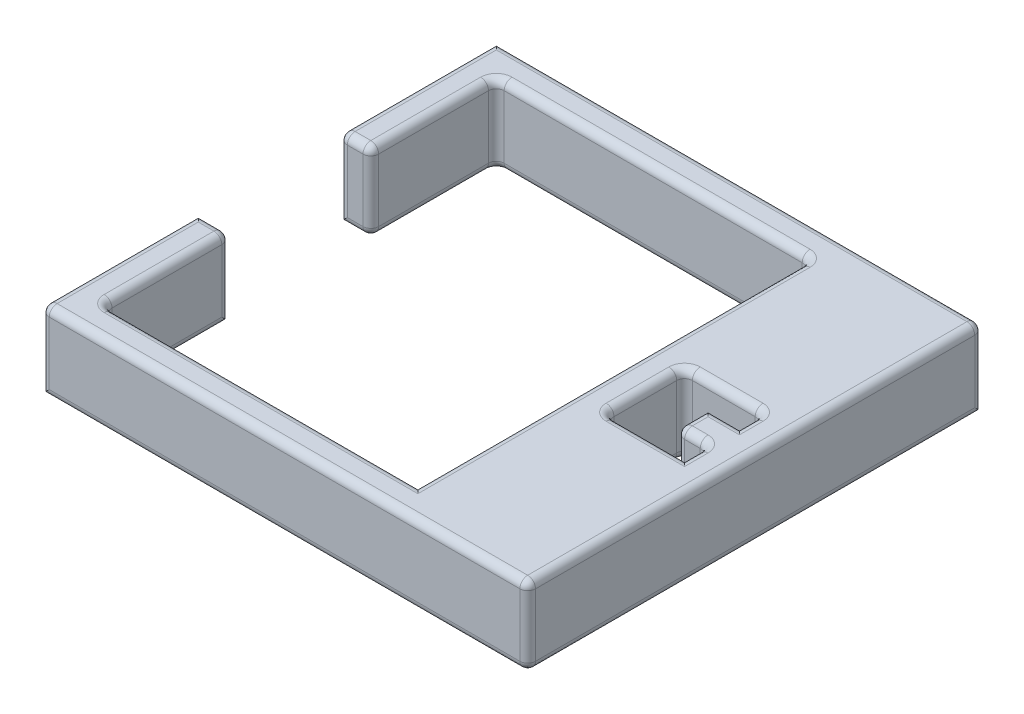
SolidWorks part; units mm, degrees
ref_plane "Front Plane" through (0, 0, 0) normal (0, 0, 1) x (1, 0, 0)
ref_plane "Top Plane" through (0, 0, 0) normal (0, 1, 0) x (1, 0, 0)
ref_plane "Right Plane" through (0, 0, 0) normal (1, 0, 0) x (0, 0, -1)
sketch "Sketch1" plane through (0, 0, 0) normal (0, 1, 0) x (1, 0, 0)
  line L0 (37.0623, -53.9428) -> (46.0623, -53.9428)
  line L1 (39.0623, -51.4428) -> (44.0623, -51.4428)
  line L2 (39.0623, -51.4428) -> (39.0623, -56.4428)
  line L3 (39.0623, -56.4428) -> (44.0623, -56.4428)
  line L4 (44.0623, -51.4428) -> (44.0623, -56.4428)
  line L5 (37.0623, -49.4428) -> (46.0623, -49.4428)
  line L6 (37.0623, -49.4428) -> (37.0623, -58.4428)
  line L7 (37.0623, -58.4428) -> (46.0623, -58.4428)
  line L8 (46.0623, -49.4428) -> (46.0623, -58.4428)
  line L9 (44.0623, -52.9428) -> (42.0623, -52.9428)
  line L10 (44.0623, -52.9428) -> (44.0623, -54.9428)
  line L11 (44.0623, -54.9428) -> (42.0623, -54.9428)
  line L12 (42.0623, -52.9428) -> (42.0623, -54.9428)
  line L25 (15.0623, -39.4428) -> (46.0623, -39.4428)
  line L27 (17.0623, -41.4428) -> (37.0623, -41.4428)
  line L29 (15.2577, -39.4428) -> (46.0623, -39.4428)
  line L30 (37.0623, -41.4428) -> (37.0623, -49.4428)
  line L31 (37.0623, -49.4428) -> (46.0623, -49.4428)
  line L32 (46.0623, -39.4428) -> (46.0623, -49.4428)
  line L34 (15.0623, -39.4428) -> (15.0623, -49.4428)
  line L35 (15.0623, -49.4428) -> (17.0623, -49.4428)
  line L36 (17.0623, -41.4428) -> (17.0623, -49.4428)
  line L37 (15.0623, -58.4428) -> (17.0623, -58.4428)
  line L38 (15.0623, -68.4428) -> (15.0623, -58.4428)
  line L39 (17.0623, -66.4428) -> (17.0623, -58.4428)
  line L40 (17.0623, -66.4428) -> (37.0623, -66.4428)
  line L41 (15.0623, -68.4428) -> (46.0623, -68.4428)
  line L42 (46.0623, -68.4428) -> (46.0623, -58.4428)
  line L43 (37.0623, -66.4428) -> (37.0623, -58.4428)
  dimension "D1" = 5
  dimension "D2" = 5
  dimension "D3" = 9
  dimension "D4" = 9
  dimension "D6" = 2
  dimension "D7" = 2
  dimension "D8" = 2
  dimension "D9" = 1.5
  dimension "D10" = 10
  dimension "D12" = 10
  dimension "D13" = 2
  dimension "D14" = 8
  dimension "D15" = 9
  dimension "D11" = 20
  dimension "D16" = 0
  dimension "D5" = 2
  dimension "D17" = 0
  dimension "D18" = 180
extrude "Boss-Extrude2" add sketch "Sketch1" along normal blind 5
fillet "Fillet1" radius 0.5 48 edges at (44.0623, 0, 55.6928) (41.5623, 0, 56.4428) (44.0623, 0, 52.1928) (37.0623, 0, 53.9428) (27.0623, 0, 66.4428) (43.0623, 0, 54.9428) (43.0623, 5, 54.9428) (42.0623, 2.5, 54.9428) (39.0623, 0, 53.9428) (41.5623, 0, 51.4428) (17.0623, 0, 45.4428) (27.0623, 0, 41.4428) (17.0623, 0, 62.4428) (30.5623, 0, 68.4428) (46.0623, 0, 53.9428) (16.0623, 0, 49.4428) (41.5623, 5, 56.4428) (39.0623, 5, 53.9428) (41.5623, 5, 51.4428) (44.0623, 5, 52.1928) (43.0623, 5, 52.9428) (42.0623, 5, 53.9428) (44.0623, 5, 55.6928) (17.0623, 5, 45.4428) (27.0623, 5, 41.4428) (37.0623, 5, 53.9428) (27.0623, 5, 66.4428) (17.0623, 5, 62.4428) (16.0623, 5, 58.4428) (15.0623, 5, 63.4428) (30.5623, 5, 68.4428) (46.0623, 5, 53.9428) (30.5623, 5, 39.4428) (15.0623, 5, 44.4428) (16.0623, 5, 49.4428) (44.0623, 2.5, 51.4428) (39.0623, 2.5, 51.4428) (39.0623, 2.5, 56.4428) (17.0623, 2.5, 49.4428) (15.0623, 2.5, 49.4428) (46.0623, 2.5, 39.4428) (46.0623, 2.5, 68.4428) (15.0623, 2.5, 68.4428) (17.0623, 2.5, 58.4428) (17.0623, 2.5, 66.4428) (37.0623, 2.5, 41.4428) (17.0623, 2.5, 41.4428) (44.0623, 2.5, 54.9428)
equation "\"ScannerWidth\"= 80"
equation "\"ScannerLength\"= 40"
equation "\"SpineLength\"= 10"
equation "\"ScannerThickness\"= 5"
equation "\"ScannerHeight\" = 5"
equation "\"SpineWidth\"= 10"
equation "\"TrainWidth\"= 4"
equation "\"TrainLength\"=2"
equation "\"Armwidth\"= 5"
equation "\"Armlength\"=100"
equation "\"RailWidth\"= 2"
equation "\"RailLength\"= 65"
equation "\"RailDepth\"=2"
equation "\"D1@Sketch1\"=\"ScannerThickness\""
equation "\"D2@Sketch1\"=\"ScannerThickness\""
equation "\"CarThickness\"= 2"
equation "\"D3@Sketch1\"=\"ScannerHeight\"+\"CarThickness\"*2"
equation "\"D4@Sketch1\"=\"ScannerThickness\"+\"CarThickness\"*2"
equation "\"D6@Sketch1\"=\"CarThickness\""
equation "\"D7@Sketch1\"=\"RailDepth\""
equation "\"D8@Sketch1\"=\"RailWidth\""
equation "\"D9@Sketch1\"=(\"ScannerThickness\"-\"RailWidth\")/2"
equation "\"CarWidth\"=5"
equation "\"ArmScanLength\"= 20"
equation "\"ArmScanWidth\"= 5"
equation "\"ArmScanHeight\"= 10"
equation "\"D10@Sketch1\"=\"ArmScanHeight\""
equation "\"D12@Sketch1\"=\"ArmScanHeight\""
equation "\"ArmScanThickness\"= 2"
equation "\"D13@Sketch1\"=\"ArmScanThickness\""
equation "\"D14@Sketch1\"=\"D12@Sketch1\"-\"ArmScanThickness\""
equation "\"D15@Sketch1\"=\"D3@Sketch1\""
equation "\"D11@Sketch1\"=\"ArmScanLength\""
equation "\"D16@Sketch1\"=0"
equation "\"D1@Boss-Extrude2\"=\"CarWidth\""
equation "\"HeadTowerHeight\"= 45"
equation "\"HeadSeparation\"= 20"
equation "\"HeadTowerRingRailWidth\"= 2"
equation "\"HeadTowerRingRailDepth\"= 2"
equation "\"HeadLength\"= 30"
equation "\"HeadScannerHeight\"=5"
equation "\"D5@Sketch1\"=\"CarThickness\""
